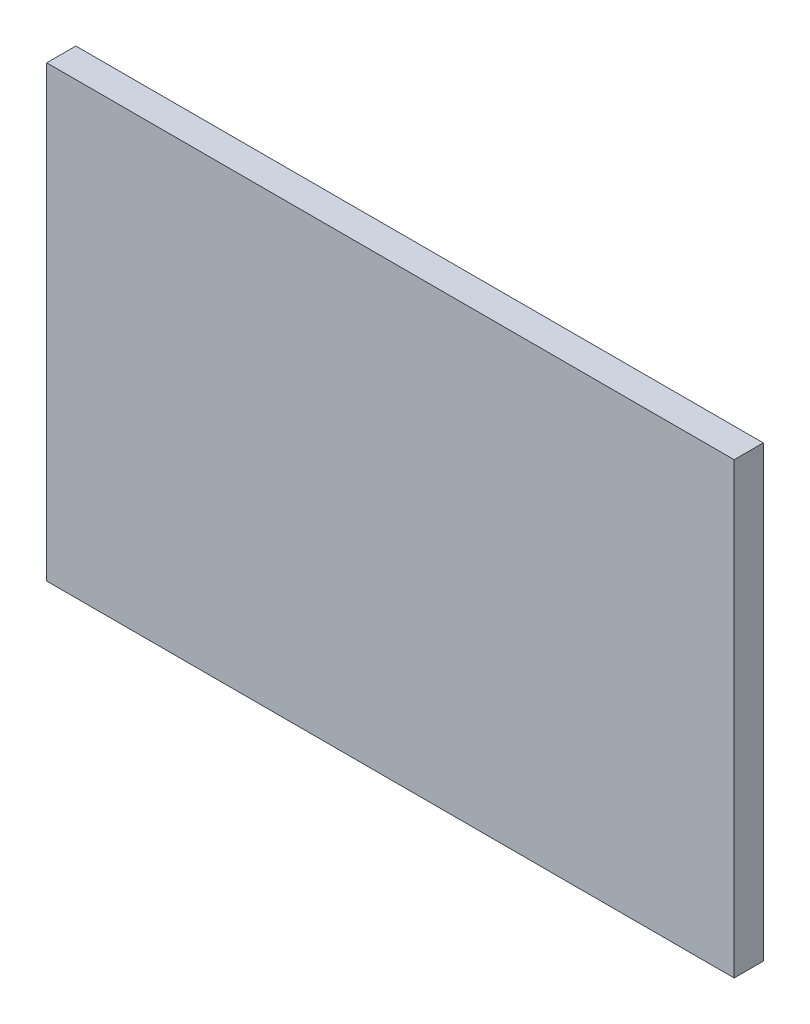
SolidWorks part; units mm, degrees
ref_plane "前视基准面" through (0, 0, 0) normal (0, 0, 1) x (1, 0, 0)
ref_plane "上视基准面" through (0, 0, 0) normal (0, 1, 0) x (1, 0, 0)
ref_plane "右视基准面" through (0, 0, 0) normal (1, 0, 0) x (0, 0, -1)
sketch "草图1" plane through (53.4975, 2.8086, 0) normal (0, 0, 1) x (1, 0, 0)
  line L1 (0, 0) -> (85, 0)
  line L2 (0, 0) -> (0, 55.5)
  line L3 (0, 55.5) -> (85, 55.5)
  line L4 (85, 0) -> (85, 55.5)
  dimension "D1" = 85
  dimension "D2" = 55.5
extrude "凸台-拉伸1" add sketch "草图1" along normal blind 3.6
